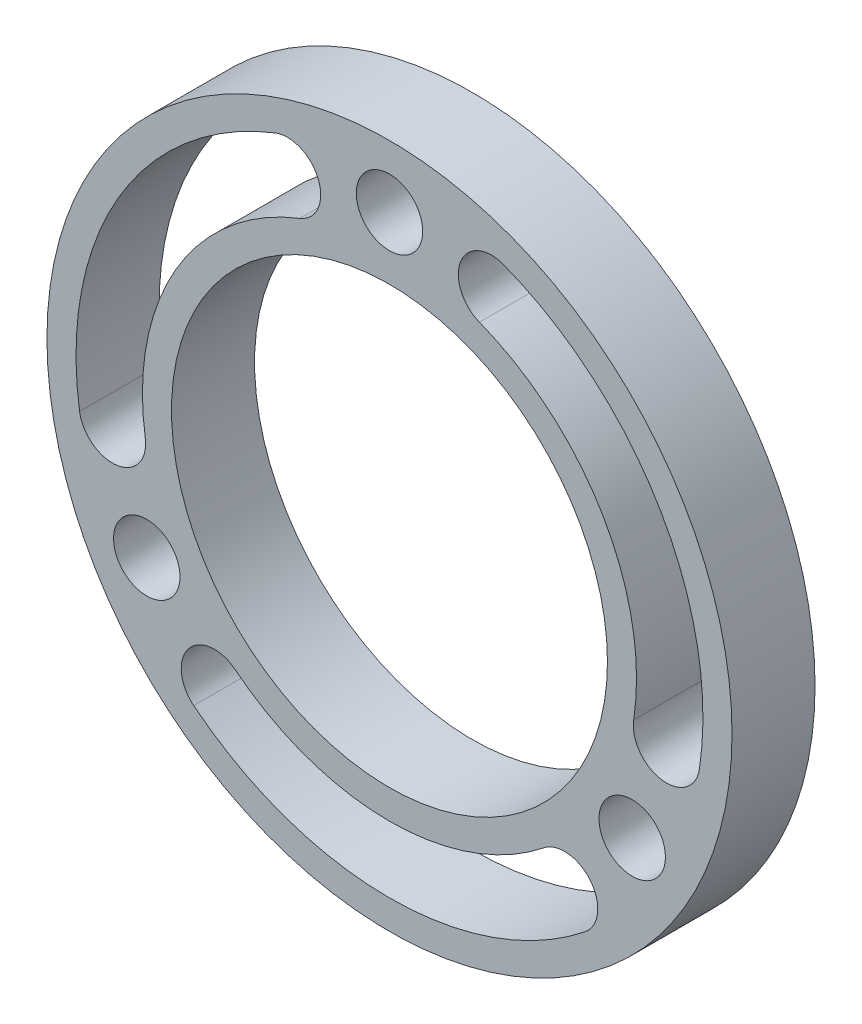
SolidWorks part; units mm, degrees
material "Thornel Mat VMA"
ref_plane "前视基准面" through (0, 0, 0) normal (0, 0, 1) x (1, 0, 0)
ref_plane "上视基准面" through (0, 0, 0) normal (0, 1, 0) x (1, 0, 0)
ref_plane "右视基准面" through (0, 0, 0) normal (1, 0, 0) x (0, 0, -1)
sketch "草图1" plane through (0, 0, 0) normal (0, 0, 1) x (1, 0, 0)
  line L0 (0, 0) -> (0, 50000) construction
  circle A0 centre (0, 0) radius 13.5 construction
  circle A1 centre (0, 0) radius 16.5
  circle A2 centre (0, 0) radius 10.5
  circle A3 centre (0, 13.5) radius 1.6
  circle A4 centre (11.6913, -6.75) radius 1.6
  circle A5 centre (-11.6913, -6.75) radius 1.6
  arc A8 (-4.3312, 11.0838) -> (-5.4959, 14.0643) centre (-4.9135, 12.5741) ccw
  arc A9 (-14.928, -2.2726) -> (-11.7645, -1.791) centre (-13.3462, -2.0318) ccw
  arc A10 (-4.3312, 11.0838) -> (-11.7645, -1.791) centre (0, 0) ccw
  arc A11 (-5.4959, 14.0643) -> (-14.928, -2.2726) centre (0, 0) ccw
  arc A12 (11.7645, -1.791) -> (14.928, -2.2726) centre (13.3462, -2.0318) ccw
  arc A13 (5.4959, 14.0643) -> (4.3312, 11.0838) centre (4.9135, 12.5741) ccw
  arc A14 (11.7645, -1.791) -> (4.3312, 11.0838) centre (0, 0) ccw
  arc A15 (14.928, -2.2726) -> (5.4959, 14.0643) centre (0, 0) ccw
  arc A16 (-7.4333, -9.2928) -> (-9.4321, -11.7917) centre (-8.4327, -10.5423) ccw
  arc A17 (9.4321, -11.7917) -> (7.4333, -9.2928) centre (8.4327, -10.5423) ccw
  arc A18 (-7.4333, -9.2928) -> (7.4333, -9.2928) centre (0, 0) ccw
  arc A19 (-9.4321, -11.7917) -> (9.4321, -11.7917) centre (0, 0) ccw
  point P15 (0, 0)
  point P35 (0, 0)
  dimension "D1" = 27
  dimension "D2" = 3
  dimension "D3" = 3
  dimension "D4" = 3.2
  dimension "D9" = 15.1
  dimension "D10" = 11.9
  dimension "D11" = 1.6
  dimension "D12" = 1.6
  dimension "D6" = 5
  dimension "D7" = 5
  dimension "D8" = 11.6913
  dimension "D5" = 3
  dimension "D13" = 3
extrude "凸台-拉伸1" add sketch "草图1" along normal blind 4
